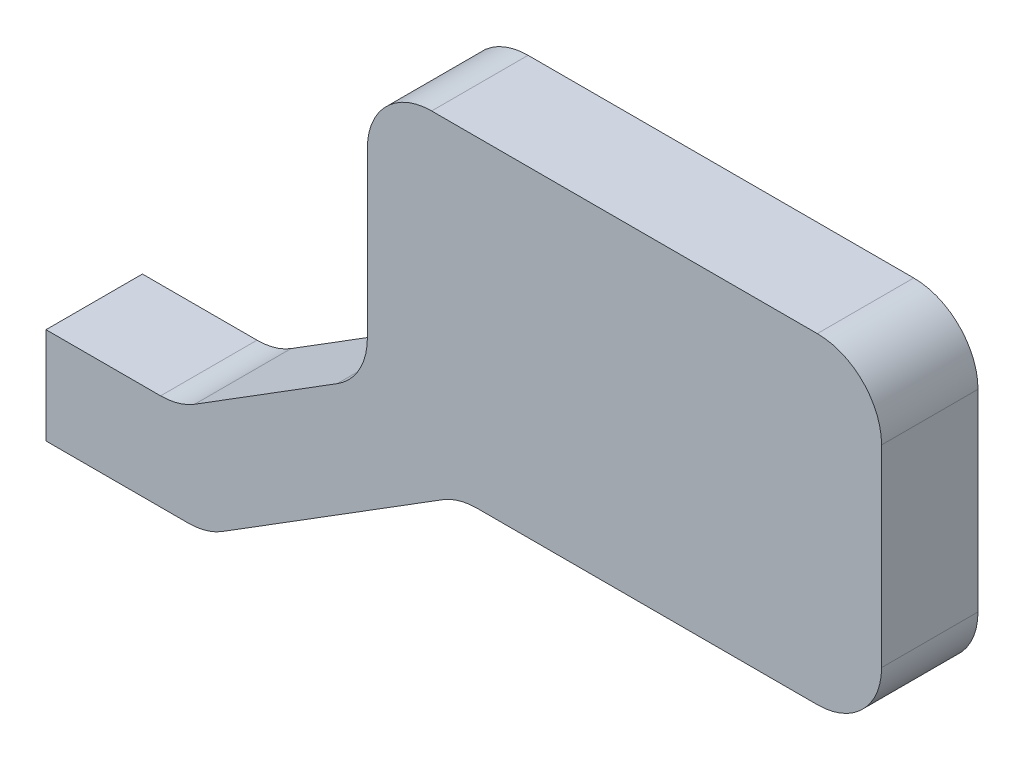
SolidWorks part; units mm, degrees
ref_plane "前视基准面" through (0, 0, 0) normal (0, 0, 1) x (1, 0, 0)
ref_plane "上视基准面" through (0, 0, 0) normal (0, 1, 0) x (1, 0, 0)
ref_plane "右视基准面" through (0, 0, 0) normal (1, 0, 0) x (0, 0, -1)
sketch "草图1" plane through (0, 0, 0) normal (0, 0, 1) x (1, 0, 0)
  line L0 (-8, -3.2311) -> (-13.8604, -6.8939)
  line L1 (-8, -5) -> (8, -5)
  line L2 (-8, -5) -> (-8, 5)
  line L3 (-8, 5) -> (8, 5)
  line L4 (8, -5) -> (8, 5)
  line L5 (-8, -5) -> (8, 5) construction
  line L6 (-8, 5) -> (8, -5) construction
  line L7 (-13.8604, -6.8939) -> (-18, -6.8939)
  line L8 (-18, -6.8939) -> (-18, -9.8939)
  line L9 (-18, -9.8939) -> (-13, -9.8939)
  line L10 (-13, -9.8939) -> (-5.1698, -5)
  point P0 (0, 0)
  dimension "D1" = 16
  dimension "D2" = 10
  dimension "D3" = 3
  dimension "D4" = 1.5
  dimension "D5" = 3
  dimension "D6" = 5
  dimension "D7" = 26
extrude "凸台-拉伸1" add sketch "草图1" along normal blind 3 contours L9 L10 L1 L2 L0 L7 L8 | L1 L4 L3 L2
fillet "圆角1" radius 2 7 edges at (-13, -9.8939, 1.5) (-13.8604, -6.8939, 1.5) (-8, -3.2311, 1.5) (-8, 5, 1.5) (-5.1698, -5, 1.5) (8, -5, 1.5) (8, 5, 1.5)
